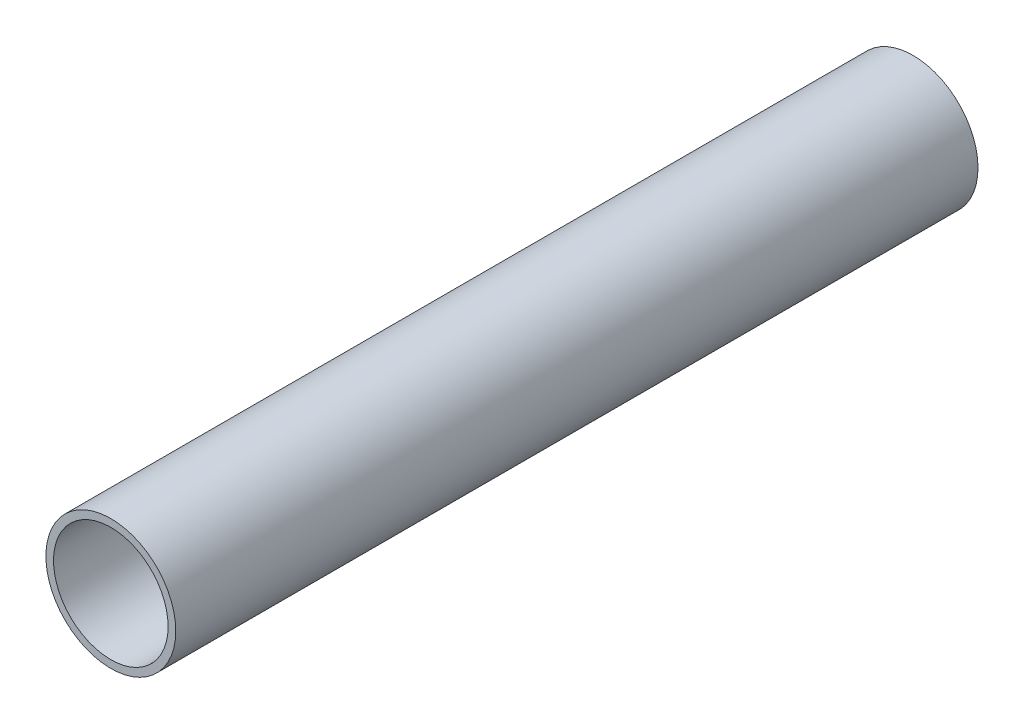
SolidWorks part; units mm, degrees
ref_plane "Front Plane" through (0, 0, 0) normal (0, 0, 1) x (1, 0, 0)
ref_plane "Top Plane" through (0, 0, 0) normal (0, 1, 0) x (1, 0, 0)
ref_plane "Right Plane" through (0, 0, 0) normal (1, 0, 0) x (0, 0, -1)
sketch "Sketch1" plane through (0, 0, 0) normal (0, 0, 1) x (1, 0, 0)
  circle A0 centre (0, 0) radius 15
  circle A1 centre (0, 0) radius 17
  dimension "D1" = 30
  dimension "D2" = 2
extrude "Boss-Extrude1" add sketch "Sketch1" along normal mid plane 210 contours A1 A0
